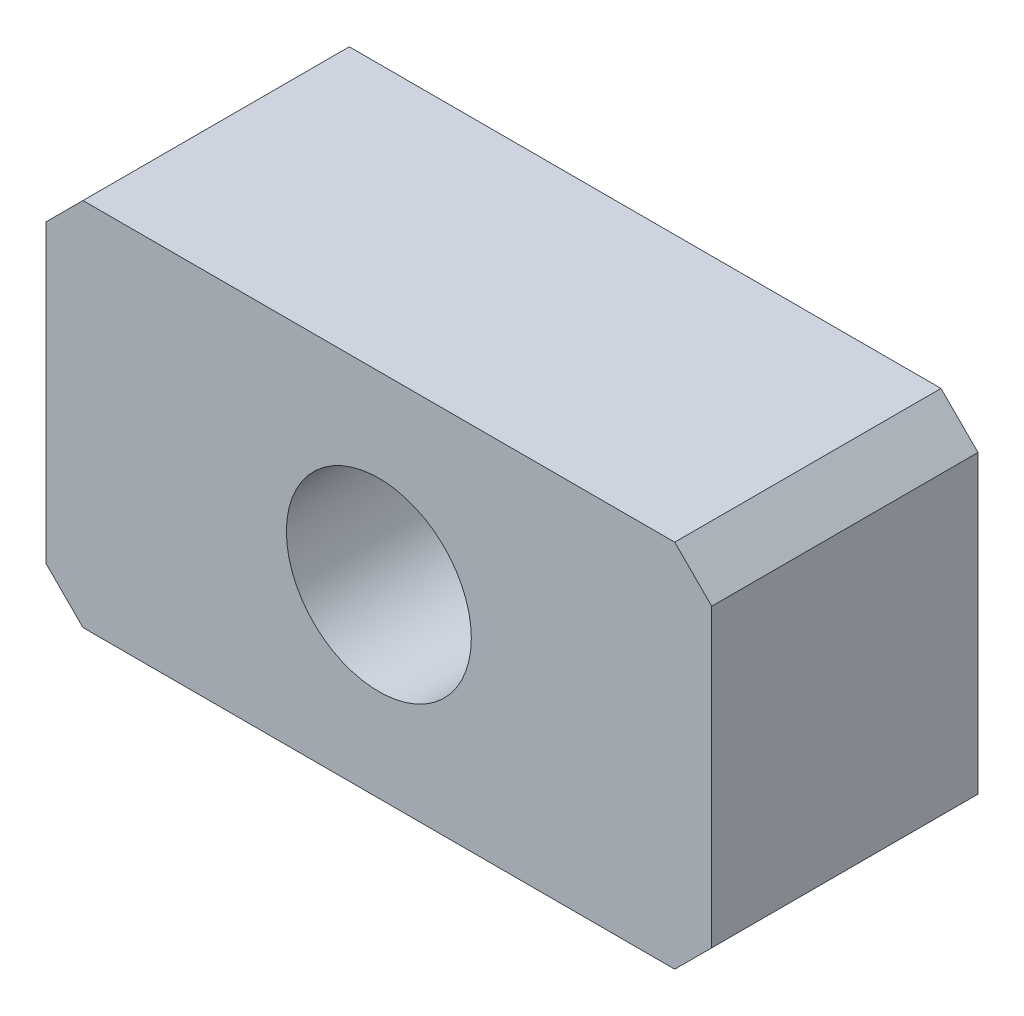
SolidWorks part; units mm, degrees
ref_plane "Front Plane" through (0, 0, 0) normal (0, 0, 1) x (1, 0, 0)
ref_plane "Top Plane" through (0, 0, 0) normal (0, 1, 0) x (1, 0, 0)
ref_plane "Right Plane" through (0, 0, 0) normal (1, 0, 0) x (0, 0, -1)
sketch "Sketch1" plane through (0, 0, 0) normal (0, 0, 1) x (1, 0, 0)
  line L1 (-9, -5) -> (9, -5)
  line L2 (-9, -5) -> (-9, 5)
  line L3 (-9, 5) -> (9, 5)
  line L4 (9, -5) -> (9, 5)
  line L5 (-9, -5) -> (9, 5) construction
  line L6 (-9, 5) -> (9, -5) construction
  circle A0 centre (0, 0) radius 2.5
  point P0 (0, 0)
  dimension "D3" = 5
  dimension "D1" = 18
  dimension "D2" = 10
extrude "Boss-Extrude1" add sketch "Sketch1" along normal blind 7.2
chamfer "Chamfer1" distance 1 angle 45 4 edges at (-9, -5, 3.6) (9, -5, 3.6) (9, 5, 3.6) (-9, 5, 3.6)
